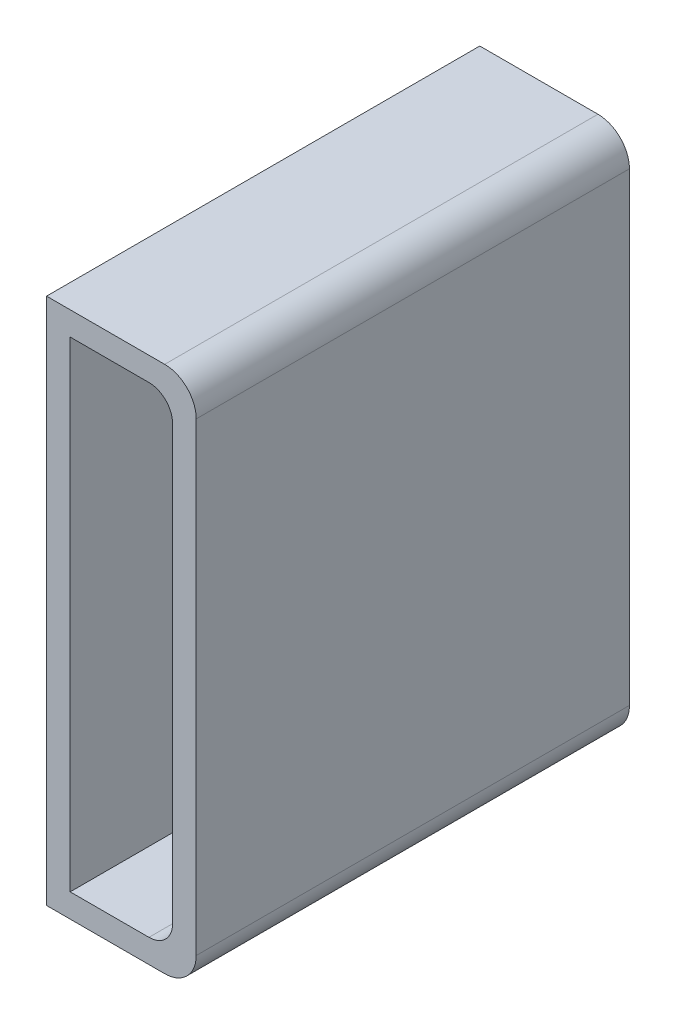
SolidWorks part; units mm, degrees
ref_plane "Front Plane" through (0, 0, 0) normal (1, 0, 0) x (0, 1, 0)
ref_plane "Top Plane" through (0, 0, 0) normal (0, 0, 1) x (0, 1, 0)
ref_plane "Right Plane" through (0, 0, 0) normal (0, 1, 0) x (-1, 0, 0)
sketch "Sketch1" plane through (0, 0, 0) normal (1, 0, 0) x (0, 1, 0)
  line L1 (-33.5, 27.5) -> (33.5, 27.5)
  line L2 (-33.5, 27.5) -> (-33.5, -27.5)
  line L3 (-33.5, -27.5) -> (33.5, -27.5)
  line L4 (33.5, 27.5) -> (33.5, -27.5)
  line L5 (-33.5, 27.5) -> (33.5, -27.5) construction
  line L6 (-33.5, -27.5) -> (33.5, 27.5) construction
  point P0 (0, 0)
  dimension "D1" = 67
  dimension "D2" = 55
extrude "Boss-Extrude1" add sketch "Sketch1" along normal blind 19
sketch "Sketch3" plane through (0, 0, 27.5) normal (0, 0, 1) x (1, 0, 0)
  line L8 (3, 30.5) -> (3, -30.5)
  line L9 (3, -30.5) -> (16, -30.5)
  line L10 (16, -30.5) -> (16, 30.5)
  line L11 (16, 30.5) -> (3, 30.5)
  line L12 (3, 30.5) -> (3, -30.5)
  line L13 (3, -30.5) -> (16, -30.5)
  line L14 (16, -30.5) -> (16, 30.5)
  line L15 (16, 30.5) -> (3, 30.5)
  dimension "D1" = 3
extrude "Cut-Extrude1" cut sketch "Sketch3" against normal offset from surface (51 mm away) 4 up to face at (9.5, 0, -27.5)
fillet "Fillet1" radius 4 2 edges at (19, 33.5, 0) (19, -33.5, 0)
fillet "Fillet2" radius 3 2 edges at (16, 30.5, 2) (16, -30.5, 2)
